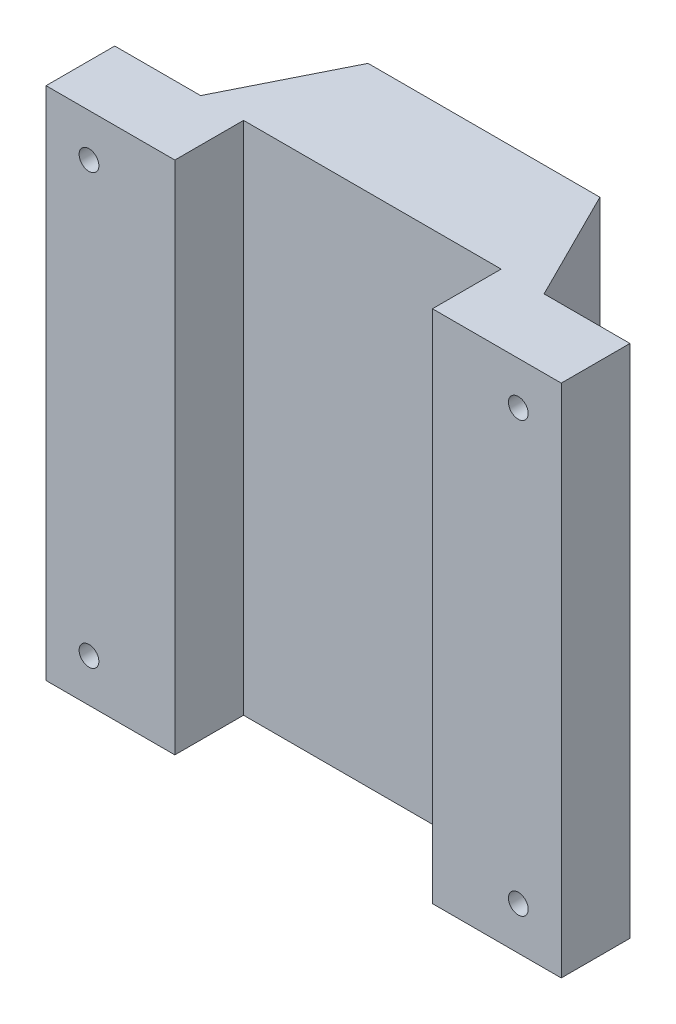
SolidWorks part; units mm, degrees
ref_plane "Front Plane" through (0, 0, 0) normal (0, 0, 1) x (1, 0, 0)
ref_plane "Top Plane" through (0, 0, 0) normal (0, 1, 0) x (1, 0, 0)
ref_plane "Right Plane" through (0, 0, 0) normal (1, 0, 0) x (0, 0, -1)
sketch "Sketch1" plane through (0, 0, 0) normal (0, 0, 1) x (1, 0, 0)
  line L1 (-30, 30) -> (30, 30)
  line L2 (-30, 30) -> (-30, -30)
  line L3 (-30, -30) -> (30, -30)
  line L4 (30, 30) -> (30, -30)
  line L5 (-30, 30) -> (30, -30) construction
  line L6 (-30, -30) -> (30, 30) construction
  point P0 (0, 0)
  dimension "D1" = 60
  dimension "D2" = 60
extrude "Boss-Extrude1" add sketch "Sketch1" along normal blind 13
sketch "Sketch2" plane through (0, 0, 13) normal (0, 0, 1) x (1, 0, 0)
  line L0 (0, 30) -> (0, -30)
  line L1 (30, 30) -> (-30, 30) construction
  line L2 (-30, -30) -> (30, -30) construction
  line L4 (-15, 30) -> (15, 30)
  line L5 (-15, 30) -> (-15, -30)
  line L6 (-15, -30) -> (15, -30)
  line L7 (15, 30) -> (15, -30)
  line L8 (-15, 30) -> (15, -30) construction
  line L9 (-15, -30) -> (15, 30) construction
  line L10 (-30, -30) -> (30, -30)
  line L11 (-30, -30) -> (-30, 30)
  line L12 (-30, 30) -> (30, 30)
  line L13 (30, -30) -> (30, 30)
  line L14 (-30, -30) -> (30, 30) construction
  line L15 (-30, 30) -> (30, -30) construction
  point P6 (0, 0)
  point P11 (0, 0)
  line M9 (30, -30) -> (30, 30)
  line M10 (30, 30) -> (-30, 30)
  line M11 (-30, 30) -> (-30, -30)
  line M12 (-30, -30) -> (30, -30)
  dimension "D1" = 30
extrude "Boss-Extrude2" add sketch "Sketch2" along normal blind 8 contours L5 M10 M11 M12 | L7 M10 M12 M9
sketch "Sketch3" plane through (0, 0, 0) normal (0, 0, -1) x (-1, 0, 0)
  line L0 (-20, 20) -> (-30, 30)
  line L1 (-30, 30) -> (-20, 30)
  line L2 (-30, 30) -> (-30, 20)
  line L3 (-30, 20) -> (-20, 20)
  line L4 (-20, 30) -> (-20, 20)
  circle A0 centre (-25, 25) radius 1.15
  circle A1 centre (25, 25) radius 1.15
  circle A2 centre (25, -25) radius 1.15
  circle A3 centre (-25, -25) radius 1.15
  point P5 (0, 0)
  point P18 (0, 0)
  dimension "D3" = 2.3
  dimension "D1" = 10
  dimension "D2" = 10
  dimension "D4" = 4
extrude "Cut-Extrude1" cut sketch "Sketch3" against normal through all contours A1 | A2 | A3 | L0 A0 | L0 A0
sketch "Sketch4" plane through (0, 0, 0) normal (0, 0, -1) x (-1, 0, 0)
  circle A0 centre (-25, 25) radius 2.2
  circle A1 centre (25, 25) radius 2.2
  circle A2 centre (25, -25) radius 2.2
  circle A3 centre (-25, -25) radius 2.2
  point P3 (0, 0)
  point P14 (0, 0)
  dimension "D1" = 4
extrude "Cut-Extrude2" cut sketch "Sketch4" against normal blind 18
sketch "Sketch6" plane through (0, 30, 0) normal (0, 1, 0) x (1, 0, 0)
  line L0 (-30, -21) -> (-30, 0) construction
  line L1 (-30, -13) -> (-20, -13)
  line L2 (-30, -13) -> (-30, -21)
  line L3 (-30, -21) -> (-20, -21)
  line L4 (-20, -13) -> (-20, -21)
  line L5 (-15, -21) -> (-30, -21) construction
  line L6 (0, -13) -> (0, 0)
  line L7 (15, -13) -> (-15, -13) construction
  line L8 (30, 0) -> (-30, 0) construction
  line L9 (-20, -13) -> (-13.5, 0)
  line L10 (-20, -13) -> (-7, -13)
  line L11 (-20, -13) -> (-20, 0)
  line L12 (-20, 0) -> (-7, 0)
  line L13 (-7, -13) -> (-7, 0)
  line L14 (30, -21) -> (20, -21)
  line L15 (20, -13) -> (20, -21)
  line L16 (30, -13) -> (20, -13)
  line L17 (30, -13) -> (30, -21)
  line L18 (20, -13) -> (13.5, 0)
  line L19 (20, 0) -> (7, 0)
  line L20 (7, -13) -> (7, 0)
  line L21 (20, -13) -> (7, -13)
  line L22 (20, -13) -> (20, 0)
  line L24 (-30, 0) -> (30, 0)
  line L25 (-30, 0) -> (-30, -21)
  line L26 (-30, -21) -> (30, -21)
  line L27 (30, 0) -> (30, -21)
  dimension "D1" = 10
extrude "Cut-Extrude4" cut sketch "Sketch6" against normal through all
